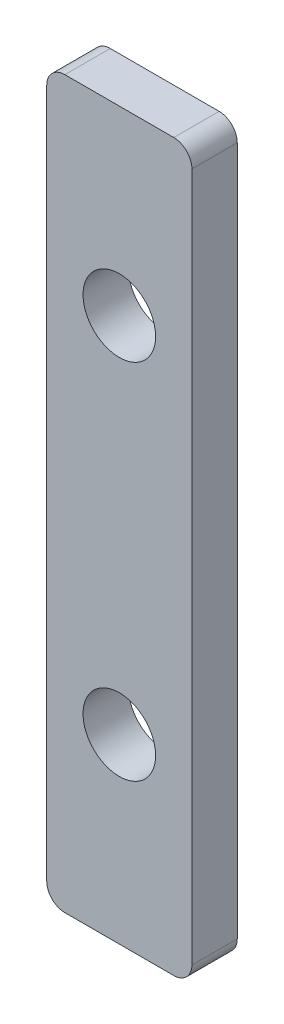
SolidWorks part; units mm, degrees
ref_plane "Front Plane" through (0, 0, 0) normal (0, 0, 1) x (1, 0, 0)
ref_plane "Top Plane" through (0, 0, 0) normal (0, 1, 0) x (1, 0, 0)
ref_plane "Right Plane" through (0, 0, 0) normal (1, 0, 0) x (0, 0, -1)
sketch "Sketch1" plane through (0, 0, 0) normal (0, 0, 1) x (1, 0, 0)
  line L0 (4, 40) -> (4, 0) construction
  line L1 (0, 0) -> (8, 0)
  line L2 (0, 0) -> (0, 40)
  line L3 (0, 40) -> (8, 40)
  line L4 (8, 0) -> (8, 40)
  circle A0 centre (4, 10) radius 2
  circle A1 centre (4, 30) radius 2
  dimension "D2" = 4
  dimension "D1" = 20
  dimension "D3" = 10
  dimension "D4" = 10
  dimension "D5" = 4
  dimension "D6" = 4
extrude "Boss-Extrude1" add sketch "Sketch1" along normal blind 2.5
fillet "Fillet1" radius 1 4 edges at (8, 0, 1.25) (0, 0, 1.25) (0, 40, 1.25) (8, 40, 1.25)
